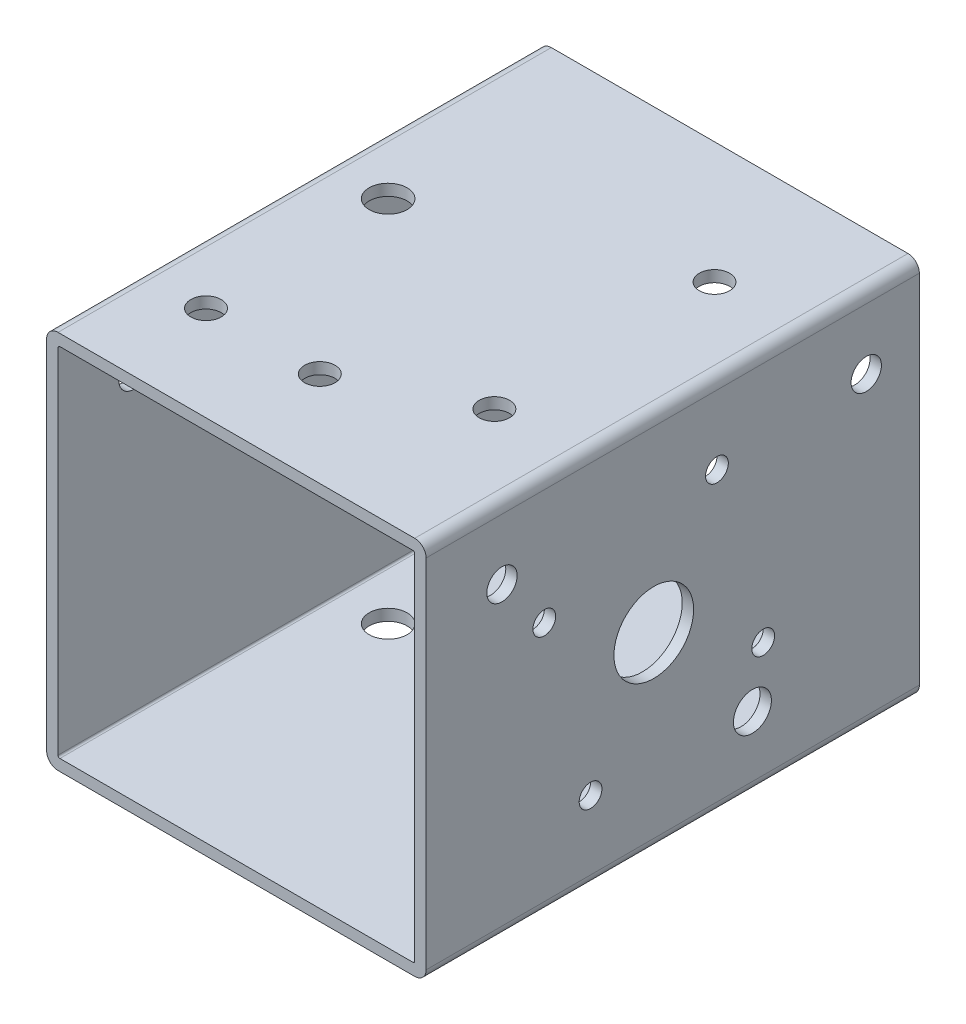
SolidWorks part; units mm, degrees
ref_plane "Front Plane" through (0, 0, 0) normal (0, 0, 1) x (1, 0, 0)
ref_plane "Top Plane" through (0, 0, 0) normal (0, 1, 0) x (1, 0, 0)
ref_plane "Right Plane" through (0, 0, 0) normal (1, 0, 0) x (0, 0, -1)
sketch "Sketch1" plane through (0, 0, 0) normal (0, 0, 1) x (1, 0, 0)
  line L1 (-50, 50) -> (50, 50)
  line L2 (-50, 50) -> (-50, -50)
  line L3 (-50, -50) -> (50, -50)
  line L4 (50, 50) -> (50, -50)
  line L5 (-50, 50) -> (50, -50) construction
  line L6 (-50, -50) -> (50, 50) construction
  point P0 (0, 0)
  dimension "D1" = 100
  dimension "D2" = 100
extrude "Extrude-Thin1" add sketch "Sketch1" along normal blind 130 thin
fillet "Fillet1" radius 0.5 4 edges at (-47, -47, 65) (-47, 47, 65) (47, 47, 65) (47, -47, 65)
fillet "Fillet2" radius 3 4 edges at (50, -50, 65) (-50, -50, 65) (50, 50, 65) (-50, 50, 65)
sketch "Holes - top" plane through (0, 0, 0) normal (0, 1, 0) x (1, 0, 0)
  line L0 (-3, 0) -> (-3, -130) construction
  line L1 (47, -130) -> (-47, -130) construction
  line L2 (-23, 0) -> (-23, -130) construction
  line L3 (47, 0) -> (-47, 0) construction
  line L4 (17, 0) -> (17, -130) construction
  circle A0 centre (-34, -56) radius 11 construction
  circle A1 centre (28, -90) radius 11 construction
  circle A2 centre (28, -32) radius 11 construction
  dimension "D4" = 22
  dimension "D1" = 40
  dimension "D2" = 40
  dimension "D3" = 32
  dimension "D5" = 56
  dimension "D6" = 3
hole_wizard "Ø8.0 (8) Diameter Hole2" positions "Sketch6" profile "Sketch5" hole size "Ø8.0" standard "ANSI Metric" end condition through all
sketch "Sketch6" plane through (0, 50, 0) normal (0, 1, 0) x (1, 0, 0)
  point P0 (28, -32)
  point P6 (28, -90)
sketch "Sketch5" plane through (28, 50, 32) normal (1, 0, 0) x (0, 0, 1)
  line L0 (0, 0) -> (0, 100)
  line L1 (0, 100) -> (4, 100)
  line L2 (4, 100) -> (4, 0)
  line L5 (4, 0) -> (0, 0)
  line L11 (0, -6.35) -> (0, 107.95) construction
  dimension "Thru Hole Dia." = 8
  dimension "Thru Hole Depth" = 100
sketch "Holes - side" plane through (0, 0, 0) normal (1, 0, 0) x (0, 0, -1)
  line L0 (0, 0) -> (-130, 0) construction
  line L1 (-130, -47) -> (-130, 47) construction
  line L2 (-130, 20) -> (0, 20) construction
  line L3 (0, -47) -> (0, 47) construction
  line L4 (-130, -20) -> (0, -20) construction
  circle A0 centre (-110, 31) radius 11 construction
  circle A1 centre (-14, 31) radius 11 construction
  circle A2 centre (-44, -31) radius 11 construction
  dimension "D1" = 40
  dimension "D2" = 22
  dimension "D3" = 20
  dimension "D4" = 14
  dimension "D5" = 44
hole_wizard "Ø8.0 (8) Diameter Hole3" positions "Sketch9" profile "Sketch8" hole size "Ø8.0" standard "ANSI Metric" end condition through all
sketch "Sketch9" plane through (50, 0, 0) normal (1, 0, 0) x (0, 0, -1)
  point P0 (-14, 31)
  point P3 (-110, 31)
sketch "Sketch8" plane through (50, 31, 14) normal (0, 1, 0) x (0, 0, -1)
  line L0 (0, 0) -> (0, 100)
  line L1 (0, 100) -> (4, 100)
  line L2 (4, 100) -> (4, 0)
  line L5 (4, 0) -> (0, 0)
  line L11 (0, -6.35) -> (0, 107.95) construction
  dimension "Thru Hole Dia." = 8
  dimension "Thru Hole Depth" = 100
hole_wizard "Ø10.0 (10) Diameter Hole1" positions "Sketch12" profile "Sketch11" hole size "Ø10.0" standard "ANSI Metric" end condition through all
sketch "Sketch12" plane through (0, 50, 0) normal (0, 1, 0) x (1, 0, 0)
  point P0 (-34, -56)
sketch "Sketch11" plane through (-34, 50, 56) normal (1, 0, 0) x (0, 0, 1)
  line L0 (0, 0) -> (0, 100)
  line L1 (0, 100) -> (5, 100)
  line L2 (5, 100) -> (5, 0)
  line L5 (5, 0) -> (0, 0)
  line L11 (0, -6.35) -> (0, 107.95) construction
  dimension "Thru Hole Dia." = 10
  dimension "Thru Hole Depth" = 100
hole_wizard "Ø10.0 (10) Diameter Hole2" positions "Sketch14" profile "Sketch13" hole size "Ø10.0" standard "ANSI Metric" end condition through all
sketch "Sketch14" plane through (50, 0, 0) normal (1, 0, 0) x (0, 0, -1)
  point P0 (-44, -31)
sketch "Sketch13" plane through (50, -31, 44) normal (0, 1, 0) x (0, 0, -1)
  line L0 (0, 0) -> (0, 100)
  line L1 (0, 100) -> (5, 100)
  line L2 (5, 100) -> (5, 0)
  line L5 (5, 0) -> (0, 0)
  line L11 (0, -6.35) -> (0, 107.95) construction
  dimension "Thru Hole Dia." = 10
  dimension "Thru Hole Depth" = 100
hole_wizard "M8x1.25 Tapped Hole1" positions "Sketch18" profile "Sketch17" tap size "M8x1.25" standard "ANSI Metric"
sketch "Sketch18" plane through (-50, 0, 0) normal (-1, 0, 0) x (0, 0, 1)
  line L0 (56, 35) -> (56, -15) construction
  point P0 (56, -15)
  point P2 (56, 35)
  dimension "D1" = 56
  dimension "D2" = 35
  dimension "D3" = 15
sketch "Sketch17" plane through (-50, -15, 56) normal (0, 1, 0) x (0, 0, 1)
  line L0 (0, 0) -> (0, 3)
  line L1 (0, 3) -> (3.4, 3)
  line L2 (3.4, 3) -> (3.4, 0)
  line L5 (3.4, 0) -> (0, 0)
  line L11 (0, -6.35) -> (0, 107.95) construction
  dimension "Thru Tap Drill Dia." = 6.8
  dimension "Thru Tap Drill Depth" = 3
cosmetic thread "Hole Thread1" parameters "D2"=8
cosmetic thread "Hole Thread2" parameters "D2"=8
hole_wizard "M8x1.25 Tapped Hole2" positions "Sketch21" profile "Sketch20" tap size "M8x1.25" standard "ANSI Metric"
sketch "Sketch21" plane through (0, -50, 0) normal (0, -1, 0) x (-1, 0, 0)
  line L0 (20, -44) -> (-35, -44) construction
  point P0 (20, -44)
  point P2 (-35, -44)
  dimension "D1" = 44
  dimension "D2" = 35
  dimension "D3" = 20
sketch "Sketch20" plane through (-20, -50, 44) normal (1, 0, 0) x (0, 0, -1)
  line L0 (0, 0) -> (0, 3)
  line L1 (0, 3) -> (3.4, 3)
  line L2 (3.4, 3) -> (3.4, 0)
  line L5 (3.4, 0) -> (0, 0)
  line L11 (0, -6.35) -> (0, 107.95) construction
  dimension "Thru Tap Drill Dia." = 6.8
  dimension "Thru Tap Drill Depth" = 3
cosmetic thread "Hole Thread3" parameters "D2"=8
cosmetic thread "Hole Thread4" parameters "D2"=8
sketch "Holes - Nema 23 motor" plane through (0, 0, 0) normal (1, 0, 0) x (0, 0, -1)
  line L0 (-98.8427, 16.6524) -> (-53.3476, 28.8427) construction
  line L1 (-98.8427, 16.6524) -> (-86.6524, -28.8427) construction
  line L2 (-53.3476, 28.8427) -> (-41.1573, -16.6524) construction
  line L3 (-86.6524, -28.8427) -> (-41.1573, -16.6524) construction
  line L4 (-98.8427, 16.6524) -> (-41.1573, -16.6524) construction
  line L5 (-53.3476, 28.8427) -> (-86.6524, -28.8427) construction
  line L6 (0, 0) -> (-130, 0) construction
  point P1 (-70, 0)
  dimension "D1" = 70
  dimension "D2" = 47.1
  dimension "D3" = 47.1
  dimension "D4" = 15
hole_wizard "Ø21.0 (21) Diameter Hole1" positions "Sketch24" profile "Sketch23" hole size "Ø21.0" standard "ANSI Metric"
sketch "Sketch24" plane through (50, 0, 0) normal (1, 0, 0) x (0, 0, -1)
  point P0 (-70, 0)
sketch "Sketch23" plane through (50, 0, 70) normal (0, 1, 0) x (0, 0, -1)
  line L0 (0, 0) -> (0, 3)
  line L1 (0, 3) -> (10.5, 3)
  line L2 (10.5, 3) -> (10.5, 0)
  line L5 (10.5, 0) -> (0, 0)
  line L11 (0, -6.35) -> (0, 107.95) construction
  dimension "Thru Hole Dia." = 21
  dimension "Thru Hole Depth" = 3
hole_wizard "Ø6.0 (6) Diameter Hole1" positions "Sketch26" profile "Sketch25" hole size "Ø6.0" standard "ANSI Metric"
sketch "Sketch26" plane through (50, 0, 0) normal (1, 0, 0) x (0, 0, -1)
  point P0 (-41.1573, -16.6524)
  point P3 (-53.3476, 28.8427)
  point P6 (-98.8427, 16.6524)
  point P9 (-86.6524, -28.8427)
sketch "Sketch25" plane through (50, -16.6524, 41.1573) normal (0, 1, 0) x (0, 0, -1)
  line L0 (0, 0) -> (0, 3)
  line L1 (0, 3) -> (3, 3)
  line L2 (3, 3) -> (3, 0)
  line L5 (3, 0) -> (0, 0)
  line L11 (0, -6.35) -> (0, 107.95) construction
  dimension "Thru Hole Dia." = 6
  dimension "Thru Hole Depth" = 3
hole_wizard "Ø8.0 (8) Diameter Hole4" positions "Sketch29" profile "Sketch28" hole size "Ø8.0" standard "ANSI Metric"
sketch "Sketch29" plane through (0, 50, 0) normal (0, 1, 0) x (1, 0, 0)
  line L0 (-3, 0) -> (-3, -130) construction
  point P0 (-3, -105)
  dimension "D1" = 15
sketch "Sketch28" plane through (-3, 50, 105) normal (1, 0, 0) x (0, 0, 1)
  line L0 (0, 0) -> (0, 3)
  line L1 (0, 3) -> (4, 3)
  line L2 (4, 3) -> (4, 0)
  line L5 (4, 0) -> (0, 0)
  line L11 (0, -6.35) -> (0, 107.95) construction
  dimension "Thru Hole Dia." = 8
  dimension "Thru Hole Depth" = 3
sketch "Sketch32" plane through (50, 0, 0) normal (1, 0, 0) x (0, 0, -1)
  line L1 (0, -47) -> (0, 47) construction
  line L2 (-65, 69.5535) -> (-65, -72.7704) construction
  line L3 (-130, -47) -> (-130, 47) construction
  line L4 (-130, 50) -> (0, 50) construction
  circle A0 centre (-5, 13) radius 2
  circle A1 centre (-5, 4) radius 2
  circle A2 centre (-125, 4) radius 2
  circle A3 centre (-125, 13) radius 2
  dimension "D1" = 46
  dimension "D2" = 9
  dimension "D3" = 4
  dimension "D5" = 5
  dimension "D4" = 0
  dimension "D6" = 65
sketch "Sketch33" plane through (0, 50, 0) normal (0, 1, 0) x (1, 0, 0)
  line L0 (47, -130) -> (-47, -130) construction
  circle A0 centre (-33, -105) radius 4
  circle A2 centre (-3, -105) radius 4 construction
  dimension "D3" = 8
  dimension "D1" = 25
  dimension "D2" = 30
extrude "Cut-Extrude1" cut sketch "Sketch33" against normal blind 10
equation "\"a\"= \"Trolley Profile@Plasma Beta.Assembly\""
equation "\"b\"= \"Trolley Profile Thickness@Plasma Beta.Assembly\""
equation "\"L\"= 130"
equation "\"D2@Sketch1\"=\"a\""
equation "\"D1@Sketch1\"=\"a\""
equation "\"D1@Extrude-Thin1\"=\"L\""
equation "\"D5@Extrude-Thin1\"=\"b\""
equation "\"D1@Fillet2\"=\"b\""
equation "\"d-bearing\"= 22'diameter of bearing"
equation "\"a-small\"= \"Beam Profile@Plasma Beta.Assembly\"'profile of smaller beam"
equation "\"D4@Holes - top\"=\"d-bearing\""
equation "\"D2@Holes - side\"=\"d-bearing\""
equation "\"D1@Holes - top\"=\"a-small\""
equation "\"D1@Holes - side\"=\"a-small\""
